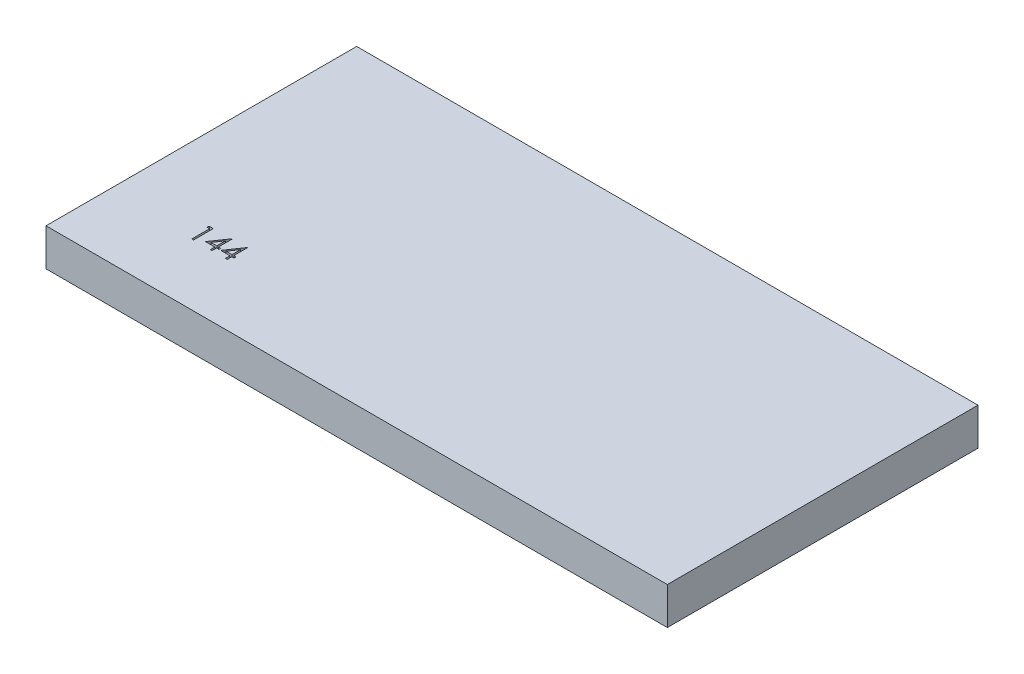
SolidWorks part; units mm, degrees
material "Acrylic (Medium-high impact)"
ref_plane "Front Plane" through (0, 0, 0) normal (0, 0, 1) x (1, 0, 0)
ref_plane "Top Plane" through (0, 0, 0) normal (0, 1, 0) x (1, 0, 0)
ref_plane "Right Plane" through (0, 0, 0) normal (1, 0, 0) x (0, 0, -1)
sketch "Sketch1" plane through (0, 0, 0) normal (0, 1, 0) x (1, 0, 0)
  line L1 (-50, 25) -> (50, 25)
  line L2 (-50, 25) -> (-50, -25)
  line L3 (-50, -25) -> (50, -25)
  line L4 (50, 25) -> (50, -25)
  line L5 (-50, 25) -> (50, -25) construction
  line L6 (-50, -25) -> (50, 25) construction
  point P0 (0, 0)
  dimension "D1" = 100
  dimension "D2" = 50
extrude "Boss-Extrude1" add sketch "Sketch1" along normal blind 6
sketch "Sketch2" plane through (0, 6, 0) normal (0, 1, 0) x (1, 0, 0)
  text T0 "144"
extrude "Cut-Extrude1" cut sketch "Sketch2" against normal blind 1
